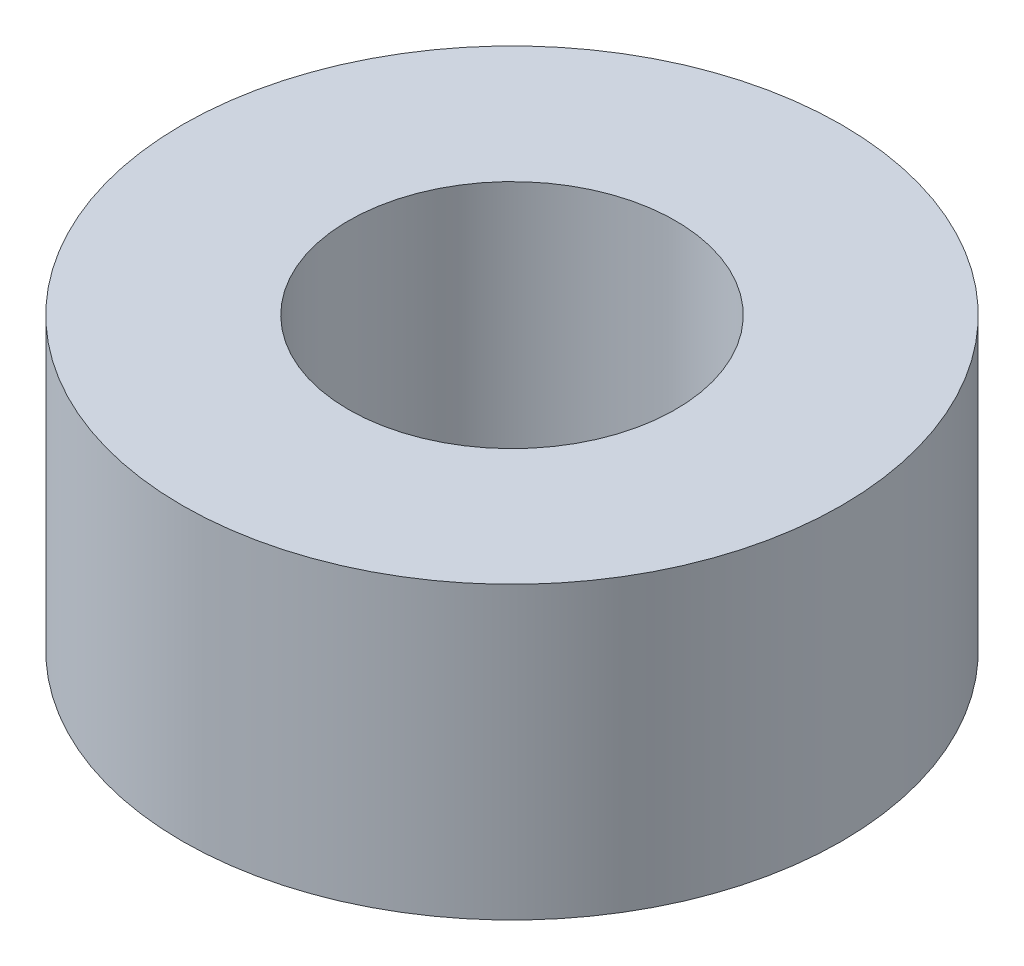
SolidWorks part; units mm, degrees
ref_plane "Front Plane" through (0, 0, 0) normal (0, 0, 1) x (1, 0, 0)
ref_plane "Top Plane" through (0, 0, 0) normal (0, 1, 0) x (1, 0, 0)
ref_plane "Right Plane" through (0, 0, 0) normal (1, 0, 0) x (0, 0, -1)
sketch "Sketch1" plane through (0, 0, 0) normal (0, 1, 0) x (1, 0, 0)
  circle A0 centre (0, 0) radius 5
  circle A1 centre (0, 0) radius 10.08
  dimension "D1" = 5.08
extrude "Boss-Extrude1" add sketch "Sketch1" along normal blind 8.89
